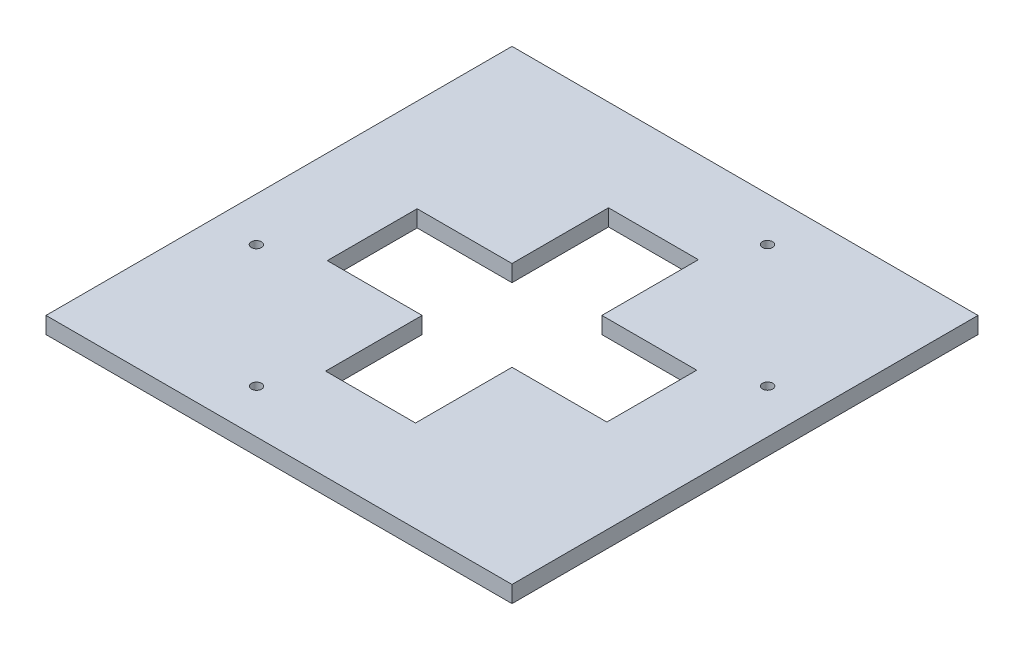
SolidWorks part; units mm, degrees
ref_plane "Front Plane" through (0, 0, 0) normal (0, 0, 1) x (1, 0, 0)
ref_plane "Top Plane" through (0, 0, 0) normal (0, 1, 0) x (1, 0, 0)
ref_plane "Right Plane" through (0, 0, 0) normal (1, 0, 0) x (0, 0, -1)
sketch "Sketch1" plane through (0, 0, 0) normal (0, 1, 0) x (1, 0, 0)
  line L1 (-70, 70) -> (70, 70)
  line L2 (-70, 70) -> (-70, -70)
  line L3 (-70, -70) -> (70, -70)
  line L4 (70, 70) -> (70, -70)
  line L5 (-70, 70) -> (70, -70) construction
  line L6 (-70, -70) -> (70, 70) construction
  point P0 (0, 0)
  dimension "D1" = 140
  dimension "D2" = 140
extrude "Boss-Extrude1" add sketch "Sketch1" along normal blind 5
sketch "Sketch2" plane through (0, 5, 0) normal (0, 1, 0) x (1, 0, 0)
  line L0 (0, 70) -> (0, -70) construction
  line L1 (70, 70) -> (-70, 70) construction
  line L2 (-70, -70) -> (70, -70) construction
  line L3 (-70, 0) -> (70, 0) construction
  line L4 (-70, 70) -> (-70, -70) construction
  line L5 (70, -70) -> (70, 70) construction
  line L6 (13, -13.5) -> (13, 13.5)
  line L7 (-42, 13.5) -> (-42, -13.5)
  line L8 (-42, -13.5) -> (-13, -13.5)
  line L9 (-13, -13.5) -> (-13, 13.5)
  line L10 (-13, 13.5) -> (-42, 13.5)
  line L11 (42, -13.5) -> (13, -13.5)
  line L12 (42, 13.5) -> (42, -13.5)
  line L13 (13, 13.5) -> (42, 13.5)
  line L14 (-13.5, 13) -> (13.5, 13)
  line L15 (-13.5, -42.4955) -> (13.5, -42.4955)
  line L16 (-13.5, -13) -> (13.5, -13)
  line L17 (13.5, -13) -> (13.5, -42.4955)
  line L18 (-13.5, -13) -> (-13.5, -42.4955)
  line L19 (-13.5, 13) -> (-13.5, 42.4955)
  line L20 (-13.5, 42.4955) -> (13.5, 42.4955)
  line L21 (13.5, 13) -> (13.5, 42.4955)
  point P16 (-42, 0)
  point P26 (0, -42.4955)
  point P32 (0, -13)
  dimension "D5" = 27
  dimension "D1" = 27
  dimension "D2" = 29
  dimension "D3" = 13
  dimension "D4" = 13.5
  dimension "D6" = 29.4955
  dimension "D7" = 13.5
  dimension "D8" = 13.5
  dimension "D9" = 13
extrude "Cut-Extrude2" cut sketch "Sketch2" against normal up to surface (5 mm away) contours L13 L21 L20 L19 L10 L9 L14 L6 | L14 L19 L10 L7 L8 L18 L16 L9 | L21 L14 L6 L16 L17 L11 L12 L13 | L8 L18 L15 L17 L11 L6 L16 L9 up to face at (0, 0, 0)
sketch "Sketch3" plane through (0, 5, 0) normal (0, 1, 0) x (1, 0, 0)
  line L0 (-13, 13) -> (-13, -13)
  line L1 (-13, -13) -> (13, -13)
  line L2 (13, -13) -> (13, 13)
  line L3 (13, 13) -> (-13, 13)
extrude "Cut-Extrude3" cut sketch "Sketch3" against normal up to surface (5 mm away) up to face at (0, 0, 0)
sketch "Sketch5" plane through (0, 5, 0) normal (0, 1, 0) x (1, 0, 0)
  circle A0 centre (-56.8, -19.9963) radius 1.525
  circle A1 centre (-19.95, -56.8037) radius 1.525
  circle A2 centre (19.95, 56.8037) radius 1.525
  circle A3 centre (56.8, 19.9963) radius 1.525
  dimension "D1" = 3.05
extrude "Cut-Extrude5" cut sketch "Sketch5" against normal up to surface (5 mm away) up to face at (0, 0, 0)
sketch "Sketch7" plane through (0, 5, 0) normal (0, 1, 0) x (1, 0, 0)
  line L0 (-13.5, -13) -> (-13.5, -13.5)
  line L1 (-13.5, -13.5) -> (-13, -13.5)
  line L2 (-13, -13.5) -> (-13, -13)
  line L3 (-13, -13) -> (-13.5, -13)
  line L4 (-13.5, 13.5) -> (-13.5, 13)
  line L5 (-13.5, 13) -> (-13, 13)
  line L6 (-13, 13) -> (-13, 13.5)
  line L7 (-13, 13.5) -> (-13.5, 13.5)
  line L8 (13, 13.5) -> (13, 13)
  line L9 (13, 13) -> (13.5, 13)
  line L10 (13.5, 13) -> (13.5, 13.5)
  line L11 (13.5, 13.5) -> (13, 13.5)
  line L12 (13, -13) -> (13, -13.5)
  line L13 (13, -13.5) -> (13.5, -13.5)
  line L14 (13.5, -13.5) -> (13.5, -13)
  line L15 (13.5, -13) -> (13, -13)
extrude "Cut-Extrude6" cut sketch "Sketch7" against normal up to surface (5 mm away) up to face at (-56.8, 0, 21.5213)
